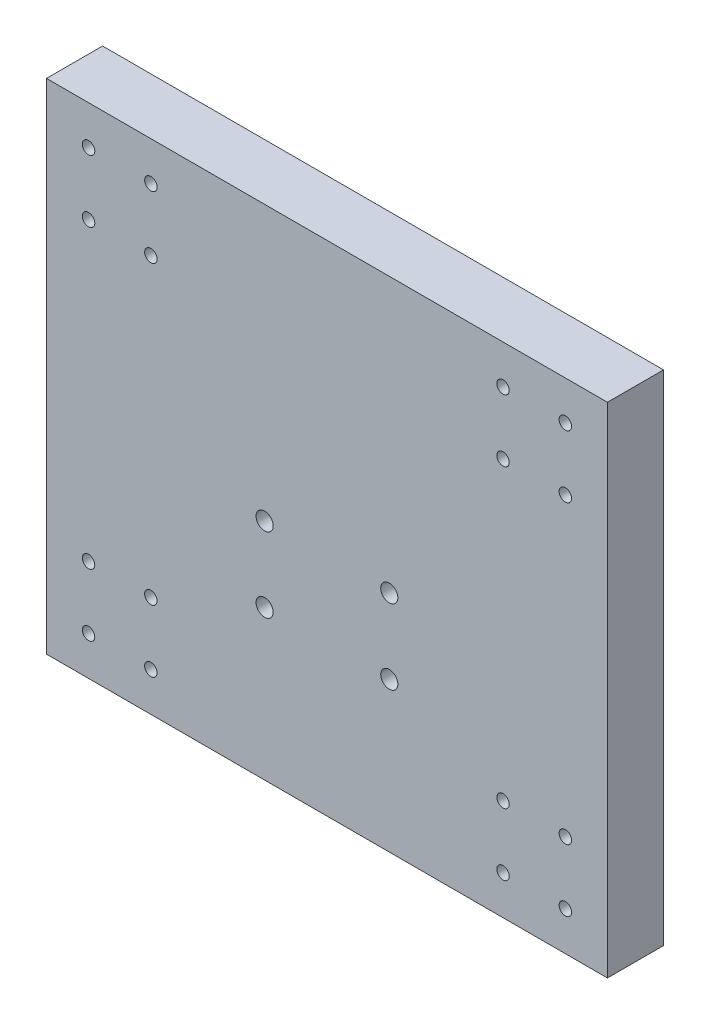
SolidWorks part; units mm, degrees
ref_plane "Front Plane" through (0, 0, 0) normal (0, 0, 1) x (1, 0, 0)
ref_plane "Top Plane" through (0, 0, 0) normal (0, 1, 0) x (1, 0, 0)
ref_plane "Right Plane" through (0, 0, 0) normal (1, 0, 0) x (0, 0, -1)
sketch "Sketch1" plane through (0, 0, 0) normal (0, 0, 1) x (1, 0, 0)
  line L1 (-80, -80) -> (80, -80)
  line L2 (-80, -80) -> (-80, 80)
  line L3 (-80, 80) -> (80, 80)
  line L4 (80, -80) -> (80, 80)
  line L5 (-80, -80) -> (80, 80) construction
  line L6 (-80, 80) -> (80, -80) construction
  point P0 (0, 0)
  dimension "D1" = 160
  dimension "D2" = 160
extrude "Boss-Extrude1" add sketch "Sketch1" against normal blind 18
sketch "Sketch2" plane through (80, 0, 0) normal (1, 0, 0) x (0, 0, -1)
  line L1 (0, 80) -> (18, 80)
  line L2 (0, 80) -> (0, -80)
  line L3 (0, -80) -> (18, -80)
  line L4 (18, 80) -> (18, -80)
extrude "Boss-Extrude2" [suppressed] add sketch "Sketch2" along normal blind 7
sketch "Sketch3" plane through (0, 0, 0) normal (0, 0, 1) x (1, 0, 0)
  line L0 (80, 80) -> (-80, 80) construction
  line L1 (-76.5, -67.5) -> (76.5, -67.5) construction
  line L2 (-76.5, -67.5) -> (-76.5, 67.5) construction
  line L3 (-76.5, 67.5) -> (76.5, 67.5) construction
  line L4 (76.5, -67.5) -> (76.5, 67.5) construction
  line L5 (-76.5, -67.5) -> (76.5, 67.5) construction
  line L6 (-76.5, 67.5) -> (76.5, -67.5) construction
  line L7 (-80, 80) -> (-80, -80) construction
  line L8 (-66.5, 67.5) -> (-66.5, 47.5) construction
  line L9 (0, 0) -> (0, 22.8286) construction
  line L10 (0, 0) -> (-23.1898, 0) construction
  line L11 (66.5, 67.5) -> (66.5, 47.5) construction
  line L12 (66.5, -67.5) -> (66.5, -47.5) construction
  line L13 (-66.5, -67.5) -> (-66.5, -47.5) construction
  line L14 (-76.5, -67.5) -> (76.5, -67.5) construction
  circle A0 centre (-76.5, 67.5) radius 2
  circle A1 centre (-76.5, 47.5) radius 2
  circle A2 centre (-56.5, 47.5) radius 2
  circle A3 centre (-56.5, 67.5) radius 2
  circle A4 centre (-76.5, 67.5) radius 2
  circle A5 centre (-76.5, 47.5) radius 2
  circle A6 centre (-56.5, 47.5) radius 2
  circle A7 centre (-56.5, 67.5) radius 2
  circle A8 centre (56.5, 67.5) radius 2
  circle A9 centre (56.5, 47.5) radius 2
  circle A10 centre (76.5, 47.5) radius 2
  circle A11 centre (76.5, 67.5) radius 2
  circle A12 centre (56.5, 67.5) radius 2
  circle A13 centre (56.5, 47.5) radius 2
  circle A14 centre (76.5, 47.5) radius 2
  circle A15 centre (76.5, 67.5) radius 2
  circle A16 centre (76.5, -67.5) radius 2
  circle A17 centre (76.5, -47.5) radius 2
  circle A18 centre (56.5, -47.5) radius 2
  circle A19 centre (56.5, -67.5) radius 2
  circle A20 centre (76.5, -67.5) radius 2
  circle A21 centre (76.5, -47.5) radius 2
  circle A22 centre (56.5, -47.5) radius 2
  circle A23 centre (56.5, -67.5) radius 2
  circle A24 centre (-56.5, -67.5) radius 2
  circle A25 centre (-56.5, -47.5) radius 2
  circle A26 centre (-76.5, -47.5) radius 2
  circle A27 centre (-76.5, -67.5) radius 2
  circle A28 centre (-56.5, -67.5) radius 2
  circle A29 centre (-56.5, -47.5) radius 2
  circle A30 centre (-76.5, -47.5) radius 2
  circle A31 centre (-76.5, -67.5) radius 2
  point P0 (0, 0)
  dimension "D4" = 4
  dimension "D5" = 4
  dimension "D1" = 12.5
  dimension "D2" = 3.5
  dimension "D3" = 20
  dimension "D6" = 10
extrude "Cut-Extrude1" cut sketch "Sketch3" against normal through all contours A0 | A3 | A2 | A1 | A11 | A10 | A17 | A16 | A18 | A19 | A25 | A24 | A26 | A27 | A8 | A9
sketch "Sketch4" plane through (0, 80, 0) normal (0, 1, 0) x (1, 0, 0)
  line L1 (80, 0) -> (90, 0)
  line L2 (80, 0) -> (80, 18)
  line L3 (80, 18) -> (90, 18)
  line L4 (90, 0) -> (90, 18)
  line L5 (-80, 18) -> (-90, 18)
  line L6 (-80, 18) -> (-80, 0)
  line L7 (-80, 0) -> (-90, 0)
  line L8 (-90, 18) -> (-90, 0)
  dimension "D1" = 10
  dimension "D2" = 10
extrude "Boss-Extrude3" add sketch "Sketch4" against normal up to surface (160 mm away) up to face at (0, -80, -9)
sketch "Sketch5" plane through (0, 0, -18) normal (0, 0, -1) x (-1, 0, 0)
  circle A0 centre (1, -9) radius 1.5
  circle A1 centre (1, -54) radius 1.5
  circle A2 centre (81, -54) radius 1.5
  circle A3 centre (81, -9) radius 1.5
  circle A4 centre (81, 9) radius 1.5
  circle A5 centre (81, 54) radius 1.5
  circle A6 centre (1, 54) radius 1.5
  circle A7 centre (1, 9) radius 1.5
extrude "Cut-Extrude2" [suppressed] cut sketch "Sketch5" against normal through all
sketch "Sketch7" plane through (0, 0, -18) normal (0, 0, -1) x (-1, 0, 0)
  line L0 (0, 0) -> (0, -32) construction
  line L1 (-20, -32) -> (20, -32) construction
  line L2 (-20, -32) -> (-20, -8) construction
  line L3 (-20, -8) -> (20, -8) construction
  line L4 (20, -32) -> (20, -8) construction
  line L5 (-20, -32) -> (20, -8) construction
  line L6 (-20, -8) -> (20, -32) construction
  line L7 (90, -80) -> (-90, -80) construction
  line L8 (0, -20) -> (-13.2323, -20) construction
  line L9 (20, -32) -> (20, -8) construction
  circle A0 centre (-20, -8) radius 2.75
  circle A1 centre (-20, -32) radius 2.75
  circle A2 centre (20, -32) radius 2.75
  circle A3 centre (20, -8) radius 2.75
  point P0 (0, -20)
  dimension "D4" = 5.5
  dimension "D1" = 40
  dimension "D2" = 24
  dimension "D3" = 48
extrude "Cut-Extrude4" cut sketch "Sketch7" against normal through all
